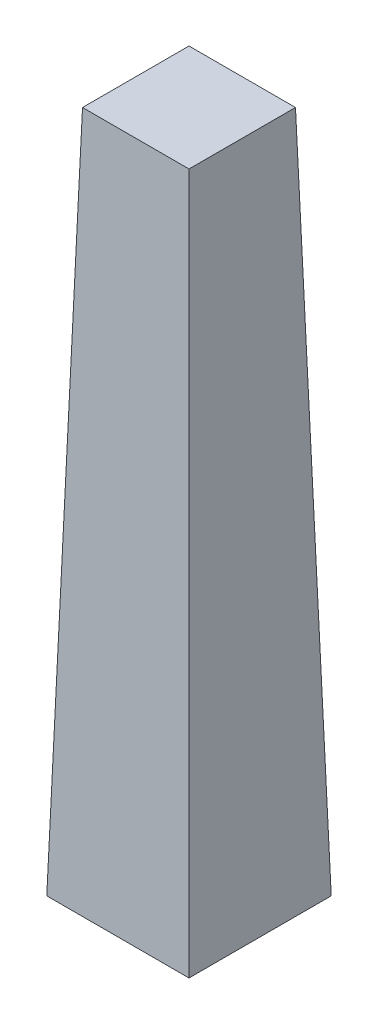
SolidWorks part; units mm, degrees
material "Pine"
ref_plane "Front" through (0, 0, 0) normal (0, 0, 1) x (1, 0, 0)
ref_plane "Top" through (0, 0, 0) normal (0, 1, 0) x (1, 0, 0)
ref_plane "Right" through (0, 0, 0) normal (1, 0, 0) x (0, 0, -1)
sketch "Sketch1" plane through (0, 0, 0) normal (0, 1, 0) x (1, 0, 0)
  line L1 (0, 0) -> (25, 0)
  line L2 (0, 0) -> (0, 25)
  line L3 (0, 25) -> (25, 25)
  line L4 (25, 0) -> (25, 25)
  dimension "D1" = 25
  dimension "D2" = 25
extrude "Boss-Extrude1" add sketch "Sketch1" along normal blind 120 draft 1.5
